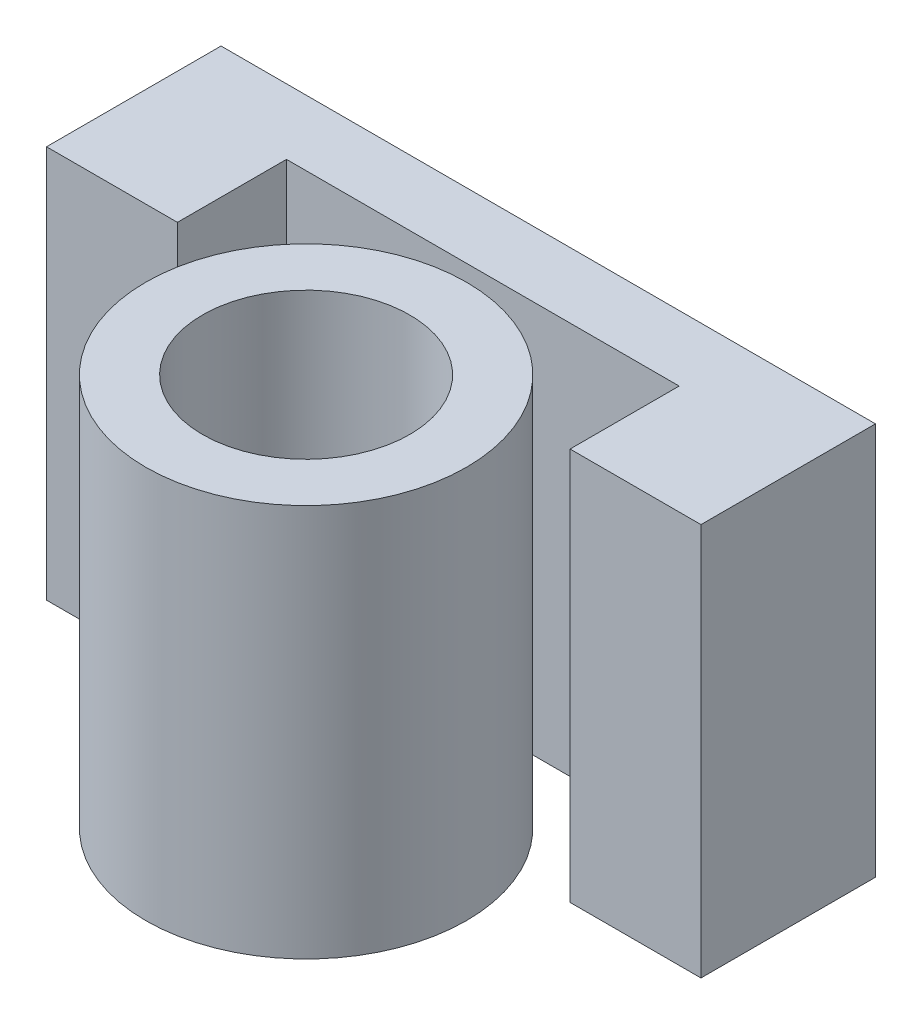
SolidWorks part; units mm, degrees
ref_plane "Front Plane" through (0, 0, 0) normal (0, 0, 1) x (1, 0, 0)
ref_plane "Top Plane" through (0, 0, 0) normal (0, 1, 0) x (1, 0, 0)
ref_plane "Right Plane" through (0, 0, 0) normal (1, 0, 0) x (0, 0, -1)
sketch "Sketch1" plane through (0, 0, 0) normal (0, 1, 0) x (1, 0, 0)
  line L0 (-15, 3.1) -> (-9, 3.1)
  line L1 (-9, 3.1) -> (-9, 8.1)
  line L2 (-9, 8.1) -> (9, 8.1)
  line L3 (-15, 3.1) -> (-15, 11.1)
  line L4 (-15, 11.1) -> (15, 11.1)
  line L5 (0, 0) -> (0, 3.1158) construction
  line L6 (9, 3.1) -> (9, 8.1)
  line L7 (15, 3.1) -> (9, 3.1)
  line L8 (15, 3.1) -> (15, 11.1)
  circle A0 centre (0, 0) radius 7.35
  circle A1 centre (0, 0) radius 4.75
  point P12 (0, 8.1)
  point P15 (0, 11.1)
  dimension "D1" = 14.7
  dimension "D2" = 9.5
  dimension "D3" = 11.1
  dimension "D4" = 3
  dimension "D5" = 6
  dimension "D6" = 15
  dimension "D7" = 8
extrude "Boss-Extrude1" add sketch "Sketch1" along normal blind 18
